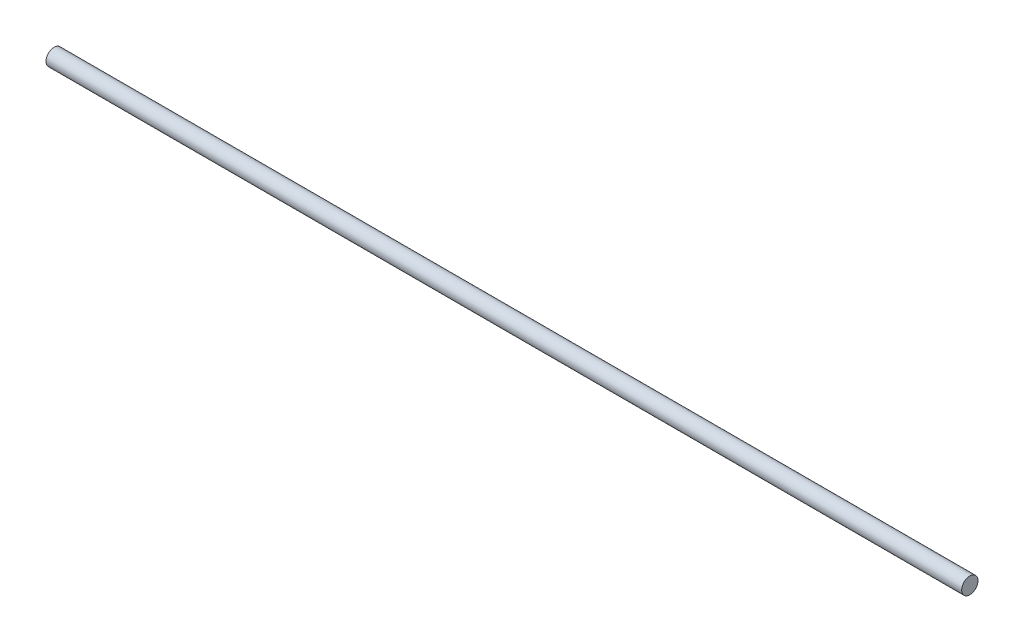
SolidWorks part; units mm, degrees
ref_plane "Front Plane" through (0, 0, 0) normal (0, 0, 1) x (1, 0, 0)
ref_plane "Top Plane" through (0, 0, 0) normal (0, 1, 0) x (1, 0, 0)
ref_plane "Right Plane" through (0, 0, 0) normal (1, 0, 0) x (0, 0, -1)
sketch "Sketch1" plane through (0, 0, 0) normal (1, 0, 0) x (0, 0, -1)
  circle A0 centre (0, 0) radius 3.175
  dimension "D1" = 6.35
extrude "Boss-Extrude1" add sketch "Sketch1" along normal blind 356
